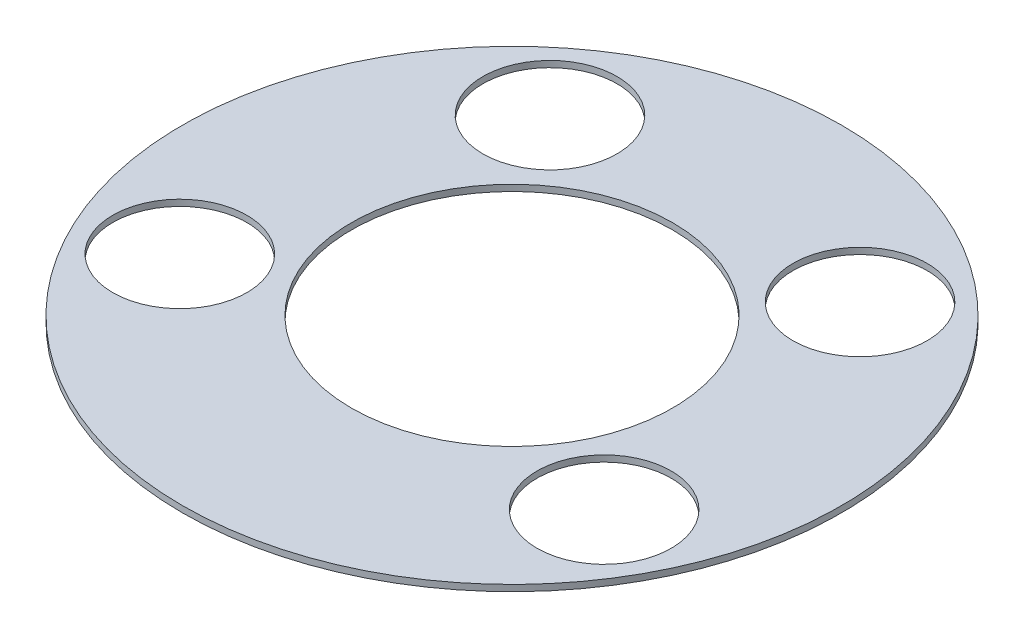
SolidWorks part; units mm, degrees
material "PTFE (general)"
ref_plane "Front Plane" through (0, 0, 0) normal (0, 0, 1) x (1, 0, 0)
ref_plane "Top Plane" through (0, 0, 0) normal (0, 1, 0) x (1, 0, 0)
ref_plane "Right Plane" through (0, 0, 0) normal (1, 0, 0) x (0, 0, -1)
sketch "Sketch1" plane through (0, 0, 0) normal (0, 1, 0) x (1, 0, 0)
  circle A0 centre (-9.2791, -5.8574) radius 25.506
  circle A1 centre (-33.7999, 24.6905) radius 10.65
  circle A2 centre (16.5241, 23.6153) radius 10.65
  circle A3 centre (-44.1081, -23.7847) radius 10.65
  circle A4 centre (24.7524, -25.2559) radius 10.65
  circle A5 centre (-9.2791, -5.8574) radius 52.338
  dimension "D1" = 104.676
extrude "Boss-Extrude2" add sketch "Sketch1" along normal blind 1
